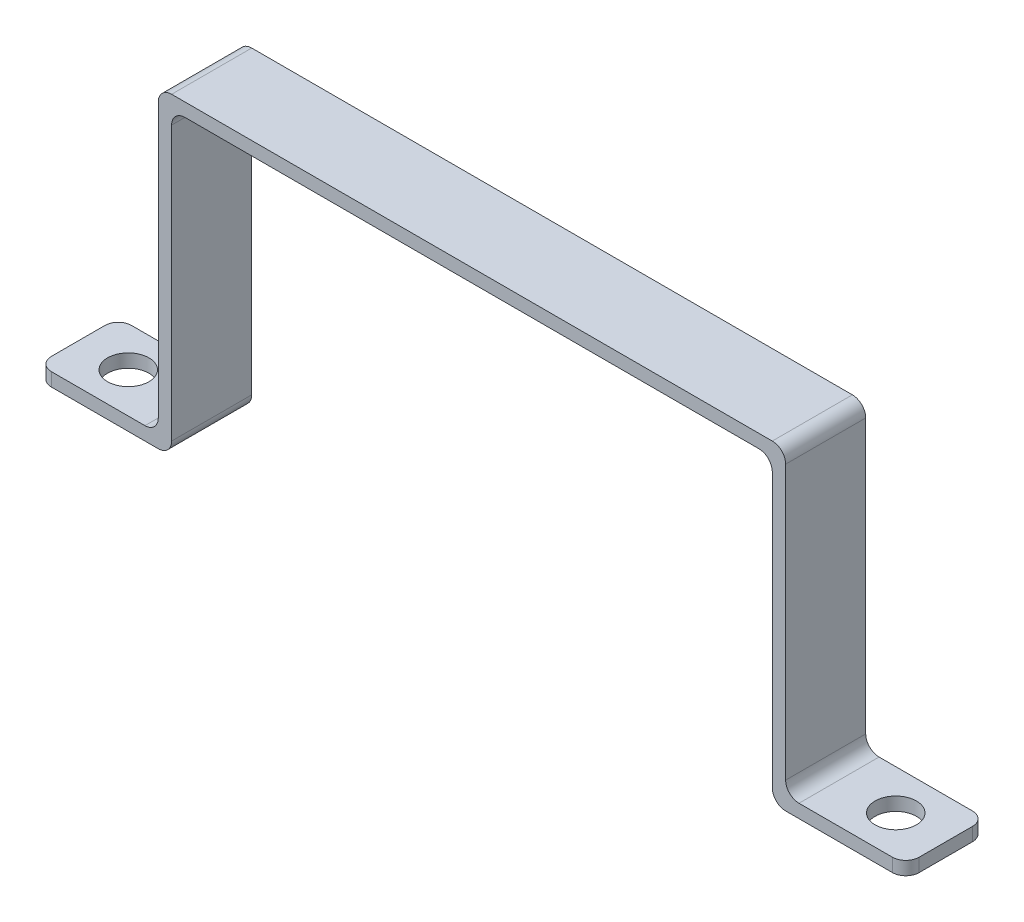
SolidWorks part; units mm, degrees
material "ABS"
ref_plane "正面" through (0, 0, 0) normal (0, 0, 1) x (1, 0, 0)
ref_plane "平面" through (0, 0, 0) normal (0, 1, 0) x (1, 0, 0)
ref_plane "右側面" through (0, 0, 0) normal (1, 0, 0) x (0, 0, -1)
sketch "ｽｹｯﾁ1" plane through (0, 0, 0) normal (0, 0, 1) x (1, 0, 0)
  line L0 (47, 0) -> (-47, 0)
  line L1 (-47, 0) -> (-47, -45)
  line L2 (-45, -47) -> (-45, -2)
  line L3 (-45, -2) -> (45, -2)
  line L4 (0, 18.8) -> (0, -22.48) construction
  line L5 (-47, -45) -> (-65, -45)
  line L6 (-45, -47) -> (-65, -47)
  line L7 (-65, -45) -> (-65, -47)
  line L8 (45, -47) -> (45, -2)
  line L9 (47, 0) -> (47, -45)
  line L10 (45, -47) -> (65, -47)
  line L11 (65, -45) -> (65, -47)
  line L12 (47, -45) -> (65, -45)
  point P13 (0, -2)
  point P14 (0, 0)
  dimension "D1" = 2
  dimension "D2" = 2
  dimension "D3" = 45
  dimension "D4" = 45
  dimension "D5" = 90
  dimension "D6" = 20
extrude "ﾎﾞｽ - 押し出し1" add sketch "ｽｹｯﾁ1" along normal blind 12
fillet "ﾌｨﾚｯﾄ1" radius 2 12 edges at (65, -46, 12) (65, -46, 0) (47, -45, 6) (45, -47, 6) (-45, -47, 6) (-45, -2, 6) (45, -2, 6) (-65, -46, 0) (-65, -46, 12) (-47, -45, 6) (-47, 0, 6) (47, 0, 6)
sketch "ｽｹｯﾁ2" plane through (0, -45, 0) normal (0, 1, 0) x (1, 0, 0)
  line L0 (-65, -6) -> (65, -6) construction
  line L1 (-65, -10) -> (-65, -2) construction
  line L2 (65, -10) -> (65, -2) construction
  line L3 (0, 0) -> (0, -12) construction
  line L4 (45, -12) -> (-45, -12) construction
  circle A0 centre (-57.5, -6) radius 3.1
  circle A1 centre (57.5, -6) radius 3.1
  dimension "D1" = 7.5
  dimension "D2" = 6.2
extrude "ｶｯﾄ - 押し出し1" cut sketch "ｽｹｯﾁ2" against normal blind 12
